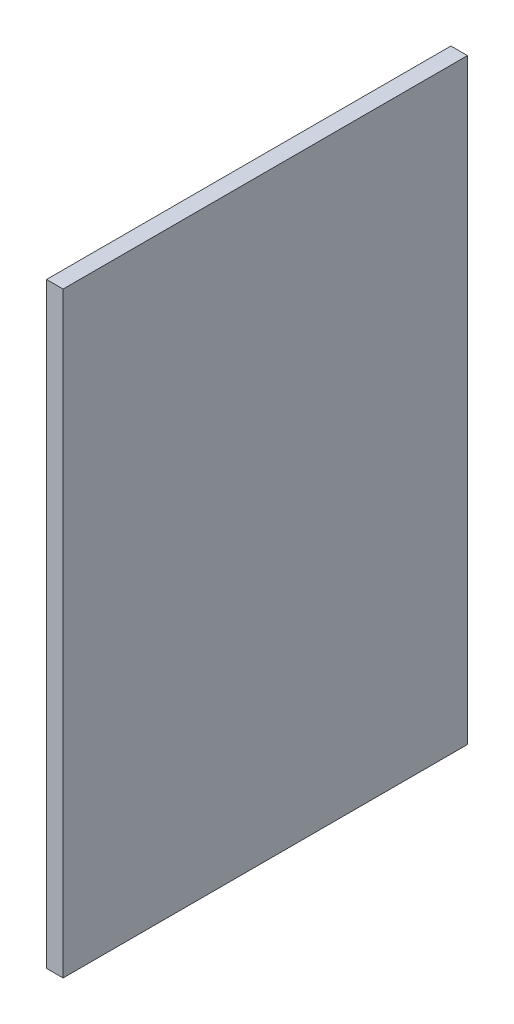
SolidWorks part; units mm, degrees
ref_plane "Front Plane" through (0, 0, 0) normal (0, 0, 1) x (1, 0, 0)
ref_plane "Top Plane" through (0, 0, 0) normal (0, 1, 0) x (1, 0, 0)
ref_plane "Right Plane" through (0, 0, 0) normal (1, 0, 0) x (0, 0, -1)
sketch "Sketch1" plane through (0, 0, 0) normal (1, 0, 0) x (0, 0, -1)
  line L1 (0, 0) -> (77.47, 0)
  line L2 (0, 0) -> (0, 114.3)
  line L3 (0, 114.3) -> (77.47, 114.3)
  line L4 (77.47, 0) -> (77.47, 114.3)
  dimension "D1" = 77.47
  dimension "D2" = 114.3
extrude "Boss-Extrude1" add sketch "Sketch1" along normal blind 3.175
